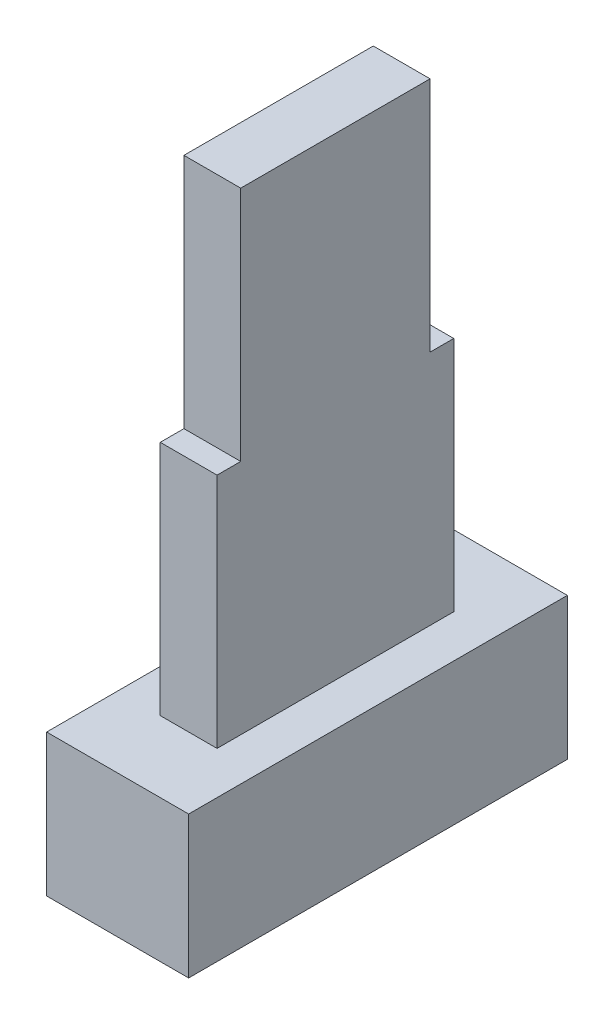
SolidWorks part; units mm, degrees
ref_plane "前视基准面" through (0, 0, 0) normal (0, 0, 1) x (1, 0, 0)
ref_plane "上视基准面" through (0, 0, 0) normal (0, 1, 0) x (1, 0, 0)
ref_plane "右视基准面" through (0, 0, 0) normal (1, 0, 0) x (0, 0, -1)
sketch "草图1" plane through (0, 0, 0) normal (0, 1, 0) x (1, 0, 0)
  line L1 (-1.5, -4) -> (1.5, -4)
  line L2 (-1.5, -4) -> (-1.5, 4)
  line L3 (-1.5, 4) -> (1.5, 4)
  line L4 (1.5, -4) -> (1.5, 4)
  line L5 (-1.5, -4) -> (1.5, 4) construction
  line L6 (-1.5, 4) -> (1.5, -4) construction
  point P0 (0, 0)
  dimension "D1" = 3
  dimension "D2" = 8
extrude "凸台-拉伸1" add sketch "草图1" along normal blind 3
sketch "草图2" plane through (0, 3, 0) normal (0, 1, 0) x (1, 0, 0)
  line L1 (0.6, -2.5) -> (-0.6, -2.5)
  line L2 (0.6, -2.5) -> (0.6, 2.5)
  line L3 (0.6, 2.5) -> (-0.6, 2.5)
  line L4 (-0.6, -2.5) -> (-0.6, 2.5)
  line L5 (0.6, -2.5) -> (-0.6, 2.5) construction
  line L6 (0.6, 2.5) -> (-0.6, -2.5) construction
  point P0 (0, 0)
  dimension "D1" = 1.2
  dimension "D2" = 5
extrude "凸台-拉伸2" add sketch "草图2" along normal blind 5
sketch "草图3" plane through (0, 8, 0) normal (0, 1, 0) x (1, 0, 0)
  line L0 (-0.6, 2.5) -> (-0.6, -2.5) construction
  line L1 (0.6, -2) -> (-0.6, -2)
  line L2 (0.6, -2) -> (0.6, 2)
  line L3 (0.6, 2) -> (-0.6, 2)
  line L4 (-0.6, -2) -> (-0.6, 2)
  line L5 (0.6, -2) -> (-0.6, 2) construction
  line L6 (0.6, 2) -> (-0.6, -2) construction
  point P0 (0, 0)
  dimension "D1" = 4
extrude "凸台-拉伸3" add sketch "草图3" along normal blind 5
